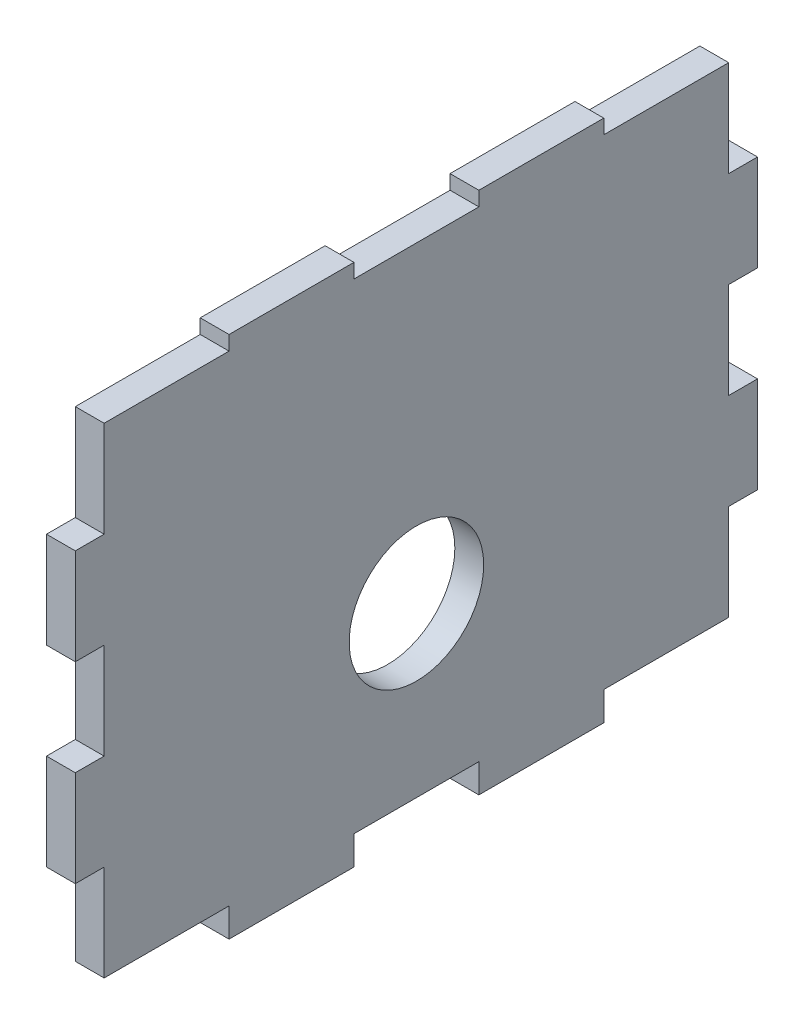
SolidWorks part; units mm, degrees
ref_plane "Front Plane" through (0, 0, 0) normal (0, 0, 1) x (1, 0, 0)
ref_plane "Top Plane" through (0, 0, 0) normal (0, 1, 0) x (1, 0, 0)
ref_plane "Right Plane" through (0, 0, 0) normal (1, 0, 0) x (0, 0, -1)
sketch "Sketch1" plane through (0, 0, 0) normal (1, 0, 0) x (0, 0, -1)
  line L0 (65, -30) -> (71, -30)
  line L1 (71, -30) -> (71, -10)
  line L2 (71, -10) -> (65, -10)
  line L3 (65, 10) -> (65, -10)
  line L4 (65, 10) -> (71, 10)
  line L5 (71, 10) -> (71, 30)
  line L6 (71, 30) -> (65, 30)
  line L7 (65, -30) -> (65, -50)
  line L8 (-65, 30) -> (-71, 30)
  line L9 (-71, 30) -> (-71, 10)
  line L10 (-71, 10) -> (-65, 10)
  line L11 (-65, -10) -> (-71, -10)
  line L12 (-71, -10) -> (-71, -30)
  line L13 (-71, -30) -> (-65, -30)
  line L14 (-65, -30) -> (-65, -50)
  line L15 (-39, -50) -> (-39, -56)
  line L16 (-39, -56) -> (-13, -56)
  line L17 (-13, -56) -> (-13, -50)
  line L18 (13, -50) -> (13, -56)
  line L19 (13, -56) -> (39, -56)
  line L20 (39, -56) -> (39, -50)
  line L21 (13, -50) -> (-13, -50)
  line L22 (-65, -50) -> (-39, -50)
  line L23 (-65, 10) -> (-65, -10)
  line L24 (39, 50) -> (65, 50)
  line L25 (-13, 50) -> (13, 50)
  line L26 (39, 53) -> (39, 50)
  line L27 (13, 53) -> (39, 53)
  line L28 (13, 50) -> (13, 53)
  line L29 (-13, 53) -> (-13, 50)
  line L30 (-39, 53) -> (-13, 53)
  line L31 (-39, 50) -> (-39, 53)
  line L32 (65, 50) -> (65, 30)
  line L33 (-39, 50) -> (-65, 50)
  line L34 (39, -50) -> (65, -50)
  line L35 (-65, 50) -> (-65, 30)
  line L36 (0, 50) -> (0, -50) construction
  circle A1 centre (0, -15) radius 14
  dimension "D27" = 28
  dimension "D28" = 35
  dimension "D1" = 20
  dimension "D2" = 20
  dimension "D3" = 20
  dimension "D4" = 20
  dimension "D5" = 6
  dimension "D6" = 6
  dimension "D7" = 20
  dimension "D8" = 20
  dimension "D9" = 20
  dimension "D10" = 6
  dimension "D11" = 6
  dimension "D12" = 26
  dimension "D13" = 26
  dimension "D14" = 26
  dimension "D15" = 26
  dimension "D16" = 26
  dimension "D17" = 6
  dimension "D18" = 6
  dimension "D19" = 6
  dimension "D20" = 6
  dimension "D21" = 3
  dimension "D22" = 3
  dimension "D23" = 3
  dimension "D24" = 3
  dimension "D25" = 26
  dimension "D26" = 26
extrude "Boss-Extrude1" add sketch "Sketch1" along normal blind 6
